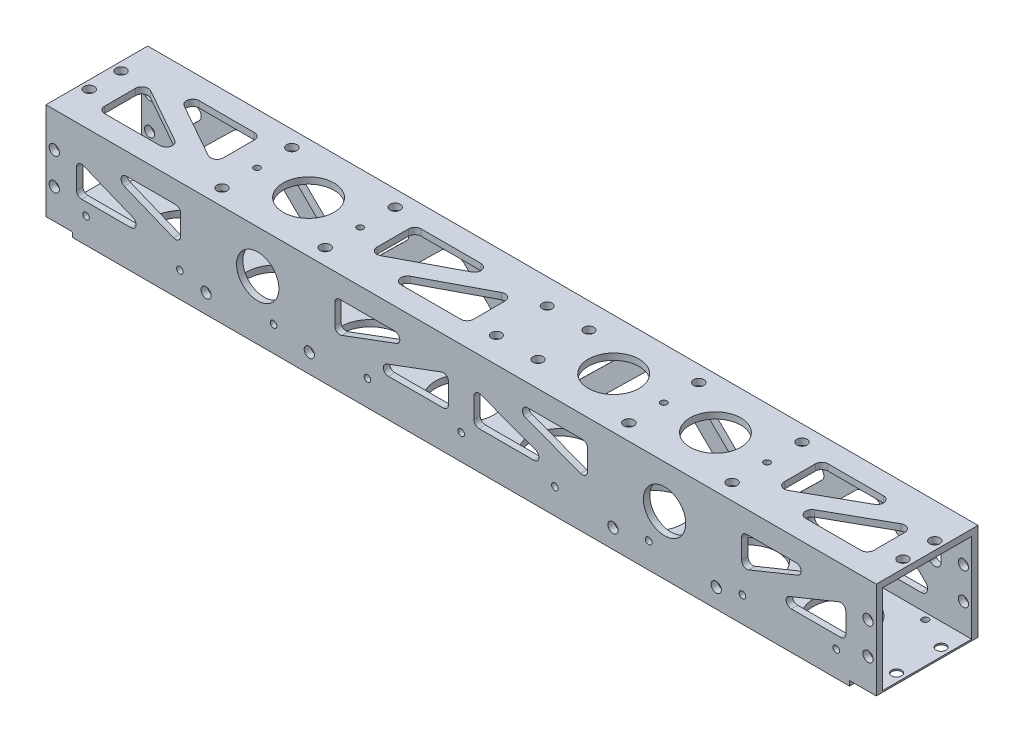
SolidWorks part; units mm, degrees
material "6061-T6 (SS)"
ref_plane "Front Plane" through (0, 0, 0) normal (0, 0, 1) x (1, 0, 0)
ref_plane "Top Plane" through (0, 0, 0) normal (0, 1, 0) x (1, 0, 0)
ref_plane "Right Plane" through (0, 0, 0) normal (1, 0, 0) x (0, 0, -1)
sketch "Sketch1" plane through (0, 0, 0) normal (1, 0, 0) x (0, 0, -1)
  line L0 (-22.225, 22.225) -> (22.225, 22.225)
  line L1 (-25.4, -25.4) -> (25.4, -25.4)
  line L2 (-25.4, -25.4) -> (-25.4, 25.4)
  line L3 (-25.4, 25.4) -> (25.4, 25.4)
  line L4 (25.4, -25.4) -> (25.4, 25.4)
  line L5 (-25.4, -25.4) -> (25.4, 25.4) construction
  line L6 (-25.4, 25.4) -> (25.4, -25.4) construction
  line L7 (22.225, -22.225) -> (22.225, 22.225)
  line L8 (-22.225, -22.225) -> (22.225, -22.225)
  line L9 (-22.225, -22.225) -> (-22.225, 22.225)
  point P0 (0, 0)
  dimension "D1" = 50.8
  dimension "D2" = 3.175
extrude "Boss-Extrude1" add sketch "Sketch1" along normal mid plane 414.655
sketch "Sketch2" plane through (0, 0, 0) normal (0, 0, 1) x (1, 0, 0)
  line L1 (-207.3275, -25.4) -> (-193.9925, -25.4)
  line L2 (-207.3275, -25.4) -> (-207.3275, -22.987)
  line L3 (-207.3275, -22.987) -> (-193.9925, -22.987)
  line L4 (-193.9925, -25.4) -> (-193.9925, -22.987)
  line L5 (207.3275, -25.4) -> (193.9925, -25.4)
  line L6 (207.3275, -25.4) -> (207.3275, -22.987)
  line L7 (207.3275, -22.987) -> (193.9925, -22.987)
  line L8 (193.9925, -25.4) -> (193.9925, -22.987)
  dimension "D1" = 2.413
  dimension "D2" = 13.335
extrude "Cut-Extrude1" cut sketch "Sketch2" against normal through all both and the other way through all
hole_wizard "#10 Clearance Hole1" positions "Sketch3" profile "Sketch4" hole size "#10" standard "ANSI Inch"
sketch "Sketch3" plane through (0, 25.4, 0) normal (0, -1, 0) x (-1, 0, 0)
  line L1 (-127.381, 17.4625) -> (127.381, 17.4625)
  line L2 (-127.381, 17.4625) -> (-127.381, -17.4625)
  line L3 (-127.381, -17.4625) -> (127.381, -17.4625)
  line L4 (127.381, 17.4625) -> (127.381, -17.4625)
  line L5 (-127.381, 17.4625) -> (127.381, -17.4625) construction
  line L6 (-127.381, -17.4625) -> (127.381, 17.4625) construction
  line L8 (-75.819, -17.4625) -> (75.819, -17.4625)
  line L9 (-75.819, -17.4625) -> (-75.819, 17.4625)
  line L10 (-75.819, 17.4625) -> (75.819, 17.4625)
  line L11 (75.819, -17.4625) -> (75.819, 17.4625)
  line L12 (-75.819, -17.4625) -> (75.819, 17.4625) construction
  line L13 (-75.819, 17.4625) -> (75.819, -17.4625) construction
  line L14 (-75.819, -17.4625) -> (-127.381, 17.4625) construction
  line L16 (0, 30.2564) -> (0, -42.6417) construction
  line L18 (-101.6, 0) -> (-101.6, 17.4625) construction
  point P2 (127.381, -17.4625)
  point P5 (-127.381, 17.4625)
  point P6 (-127.381, -17.4625)
  point P7 (127.381, 17.4625)
  point P51 (0, 0)
  point P68 (75.819, 17.4625)
  point P71 (-75.819, -17.4625)
  point P72 (-75.819, 17.4625)
  point P73 (75.819, -17.4625)
  dimension "D1" = 203.2
  dimension "D2" = 34.925
  dimension "D3" = 51.562
sketch "Sketch4" plane through (-127.381, 25.4, 17.4625) normal (1, 0, 0) x (0, 0, 1)
  line L0 (0, 0) -> (0, 4.7078)
  line L1 (0, 4.7078) -> (2.5527, 3.174)
  line L2 (2.5527, 3.174) -> (2.5527, 0)
  line L5 (2.5527, 0) -> (0, 0)
  line L10 (0, 4.7078) -> (-2.5527, 3.174) construction
  line L11 (0, -6.35) -> (0, 107.95) construction
  dimension "Hole Dia." = 5.1054
  dimension "Hole Depth" = 3.174
  dimension "Drill Angle" = 118
sketch "Sketch5" plane through (0, -25.4, 0) normal (0, -1, 0) x (1, 0, 0)
  circle A0 centre (-127.381, 17.4625) radius 4.7625
  circle A1 centre (-127.381, -17.4625) radius 4.7625
  circle A2 centre (127.381, -17.4625) radius 4.7625
  circle A3 centre (127.381, 17.4625) radius 4.7625
  circle A4 centre (-75.819, 17.4625) radius 4.7625
  circle A5 centre (-75.819, -17.4625) radius 4.7625
  circle A6 centre (75.819, -17.4625) radius 4.7625
  circle A7 centre (75.819, 17.4625) radius 4.7625
  dimension "D1" = 9.525
extrude "Cut-Extrude2" [suppressed] cut sketch "Sketch5" against normal up to next
hole_wizard "#10 Clearance Hole2" positions "Sketch6" profile "Sketch7" hole size "#10" standard "ANSI Inch"
sketch "Sketch6" plane through (0, 0, 25.4) normal (0, 0, -1) x (-1, 0, 0)
  line L0 (-127.381, 25.4) -> (-127.381, -25.4) construction
  line L1 (-207.3275, 25.4) -> (207.3275, 25.4) construction
  line L2 (-193.9925, -25.4) -> (193.9925, -25.4) construction
  line L4 (127.381, 25.4) -> (127.381, -25.4) construction
  line L6 (-124.8283, 25.4) -> (-129.9337, 25.4) construction
  line L7 (129.9337, 25.4) -> (124.8283, 25.4) construction
  line L8 (-75.819, 25.4) -> (-75.819, -25.4) construction
  line L10 (75.819, 25.4) -> (75.819, -25.4) construction
  line L15 (78.3717, 25.4) -> (73.2663, 25.4) construction
  line L16 (-73.2663, 25.4) -> (-78.3717, 25.4) construction
  point P15 (-127.381, -15.875)
  point P17 (127.381, -15.875)
  point P49 (-75.819, -15.875)
  point P51 (75.819, -15.875)
  dimension "D1" = 9.525
sketch "Sketch7" plane through (-75.819, -15.875, 25.4) normal (1, 0, 0) x (0, -1, 0)
  line L0 (0, 0) -> (0, 3.175)
  line L1 (0, 3.175) -> (2.5527, 3.175)
  line L2 (2.5527, 3.175) -> (2.5527, 0)
  line L5 (2.5527, 0) -> (0, 0)
  line L11 (0, -6.35) -> (0, 107.95) construction
  dimension "Thru Hole Dia." = 5.1054
  dimension "Thru Hole Depth" = 3.175
hole_wizard "#10 Clearance Hole3" positions "Sketch9" profile "Sketch10" hole size "#10" standard "ANSI Inch"
sketch "Sketch9" plane through (0, 25.4, 0) normal (0, 1, 0) x (1, 0, 0)
  line L1 (-203.2, -7.9375) -> (203.2, -7.9375)
  line L2 (-203.2, -7.9375) -> (-203.2, 7.9375)
  line L3 (-203.2, 7.9375) -> (203.2, 7.9375)
  line L4 (203.2, -7.9375) -> (203.2, 7.9375)
  line L5 (-203.2, -7.9375) -> (203.2, 7.9375) construction
  line L6 (-203.2, 7.9375) -> (203.2, -7.9375) construction
  point P2 (203.2, 7.9375)
  point P5 (-203.2, -7.9375)
  point P6 (-203.2, 7.9375)
  point P7 (203.2, -7.9375)
  point P42 (0, 0)
  dimension "D1" = 15.875
  dimension "D2" = 406.4
sketch "Sketch10" plane through (203.2, 25.4, -7.9375) normal (1, 0, 0) x (0, 0, 1)
  line L0 (0, 0) -> (0, 3.175)
  line L1 (0, 3.175) -> (2.5527, 3.175)
  line L2 (2.5527, 3.175) -> (2.5527, 0)
  line L5 (2.5527, 0) -> (0, 0)
  line L11 (0, -6.35) -> (0, 107.95) construction
  dimension "Thru Hole Dia." = 5.1054
  dimension "Thru Hole Depth" = 3.175
hole_wizard "#10 Clearance Hole4" positions "Sketch11" profile "Sketch12" hole size "#10" standard "ANSI Inch" end condition through all
sketch "Sketch11" plane through (0, 0, 25.4) normal (0, 0, 1) x (1, 0, 0)
  line L1 (-203.2, 7.9375) -> (203.2, 7.9375)
  line L2 (-203.2, 7.9375) -> (-203.2, -7.9375)
  line L3 (-203.2, -7.9375) -> (203.2, -7.9375)
  line L4 (203.2, 7.9375) -> (203.2, -7.9375)
  line L5 (-203.2, 7.9375) -> (203.2, -7.9375) construction
  line L6 (-203.2, -7.9375) -> (203.2, 7.9375) construction
  line L7 (-203.2, 7.9375) -> (-203.2, 25.4) construction
  line L8 (207.3275, 25.4) -> (-207.3275, 25.4) construction
  line L10 (-200.6473, 25.4) -> (-205.7527, 25.4) construction
  point P2 (203.2, -7.9375)
  point P5 (-203.2, 7.9375)
  point P6 (-203.2, -7.9375)
  point P7 (203.2, 7.9375)
  point P54 (0, 0)
  dimension "D1" = 15.875
sketch "Sketch12" plane through (203.2, -7.9375, 25.4) normal (1, 0, 0) x (0, -1, 0)
  line L0 (0, 0) -> (0, 50.8)
  line L1 (0, 50.8) -> (2.5527, 50.8)
  line L2 (2.5527, 50.8) -> (2.5527, 0)
  line L5 (2.5527, 0) -> (0, 0)
  line L11 (0, -6.35) -> (0, 107.95) construction
  dimension "Thru Hole Dia." = 5.1054
  dimension "Thru Hole Depth" = 50.8
hole_wizard "Hole1" positions "Sketch15" profile "Sketch16" legacy end condition up to next
sketch "Sketch15" plane through (0, -25.4, 0) normal (0, -1, 0) x (-1, 0, 0)
  line L1 (187.325, -19.05) -> (-187.325, -19.05)
  line L2 (187.325, -19.05) -> (187.325, 19.05)
  line L3 (187.325, 19.05) -> (-187.325, 19.05)
  line L4 (-187.325, -19.05) -> (-187.325, 19.05)
  line L5 (187.325, -19.05) -> (-187.325, 19.05) construction
  line L6 (187.325, 19.05) -> (-187.325, -19.05) construction
  point P5 (187.325, -19.05)
  point P6 (187.325, 19.05)
  point P42 (0, 0)
  point P52 (140.4938, -19.05)
  point P53 (140.4938, 19.05)
  point P54 (93.6625, -19.05)
  point P55 (93.6625, 19.05)
  point P56 (46.8312, -19.05)
  point P57 (46.8312, 19.05)
  point P58 (0, -19.05)
  point P59 (0, 19.05)
  point P60 (-46.8312, -19.05)
  point P61 (-46.8312, 19.05)
  point P62 (-93.6625, -19.05)
  point P63 (-93.6625, 19.05)
  point P64 (-140.4938, -19.05)
  point P65 (-140.4938, 19.05)
  point P66 (-187.325, -19.05)
  point P67 (-187.325, 19.05)
  dimension "D1" = 38.1
  dimension "D2" = 374.65
  dimension "D3" = 9
sketch "Sketch16" plane through (187.325, -25.4, -19.05) normal (1, 0, 0) x (0, 0, -1)
  line L0 (0, 0) -> (0, 4.1594)
  line L1 (0, 4.1594) -> (1.6383, 3.175)
  line L2 (1.6383, 3.175) -> (1.6383, 0)
  line L4 (1.6383, 0) -> (0, 0)
  line L6 (0, 4.1594) -> (-1.6383, 3.175) construction
  line L7 (0, -4.2442) -> (0, 117.3081) construction
  dimension "Diameter" = 3.2766
  dimension "Depth" = 3.175
  dimension "Drill Angle" = 118
hole_wizard "Hole2" positions "Sketch17" profile "Sketch18" legacy
sketch "Sketch17" plane through (0, 0, 25.4) normal (0, 0, 1) x (1, 0, 0)
  line L0 (-187.325, -12.7) -> (187.325, -12.7) construction
  line L2 (0, -12.7) -> (0, 0) construction
  line L3 (193.9925, -25.4) -> (-193.9925, -25.4) construction
  line L4 (-187.325, -12.7) -> (-187.325, -25.4) construction
  line L6 (-188.9633, -25.4) -> (-185.6867, -25.4) construction
  point P1 (-187.325, -12.7)
  point P25 (-140.4938, -12.7)
  point P26 (-93.6625, -12.7)
  point P27 (-46.8312, -12.7)
  point P28 (0, -12.7)
  point P29 (46.8312, -12.7)
  point P30 (93.6625, -12.7)
  point P31 (140.4938, -12.7)
  point P32 (187.325, -12.7)
  dimension "D1" = 12.7
  dimension "D2" = 9
sketch "Sketch18" plane through (-187.325, -12.7, 25.4) normal (1, 0, 0) x (0, -1, 0)
  line L0 (0, 0) -> (0, 3.175)
  line L1 (0, 3.175) -> (1.6383, 3.175)
  line L2 (1.6383, 3.175) -> (1.6383, 0)
  line L3 (1.6383, 0) -> (0, 0)
  line L4 (0, 110) -> (0, -10) construction
  dimension "Diameter" = 3.2766
  dimension "Depth" = 3.175
sketch "Sketch19" plane through (0, 25.4, 0) normal (0, 1, 0) x (1, 0, 0)
  line L0 (-127.381, 17.4625) -> (-127.381, -17.4625) construction
  line L1 (127.381, 17.4625) -> (127.381, -17.4625) construction
  line L2 (-75.819, 17.4625) -> (-75.819, -17.4625) construction
  line L3 (75.819, 17.4625) -> (75.819, -17.4625) construction
  circle A0 centre (127.381, 0) radius 1.5748
  circle A1 centre (-127.381, 0) radius 1.5748
  circle A3 centre (-75.819, 17.4625) radius 2.5527 construction
  circle A4 centre (-75.819, 0) radius 1.5748
  circle A5 centre (75.819, 0) radius 1.5748
  dimension "D1" = 3.1496
extrude "Cut-Extrude4" cut sketch "Sketch19" against normal up to next
hole_wizard "#10 Clearance Hole5" positions "Sketch21" profile "Sketch22" hole size "#10" standard "ANSI Inch"
sketch "Sketch21" plane through (0, -22.987, 0) normal (0, -1, 0) x (-1, 0, 0)
  line L0 (-203.2, -11.1125) -> (-203.2, 11.1125) construction
  line L2 (-207.3275, 25.4) -> (-207.3275, -25.4) construction
  line L3 (-203.2, 0) -> (-207.3275, 0) construction
  line L5 (207.3275, 0) -> (203.2, 0) construction
  line L6 (207.3275, 25.4) -> (207.3275, -25.4) construction
  line L8 (203.2, -11.1125) -> (203.2, 11.1125) construction
  point P0 (-203.2, -11.1125)
  point P4 (-203.2, 11.1125)
  point P18 (203.2, -11.1125)
  point P19 (203.2, 11.1125)
  dimension "D1" = 4.1275
  dimension "D2" = 22.225
sketch "Sketch22" plane through (203.2, -22.987, 11.1125) normal (1, 0, 0) x (0, 0, -1)
  line L0 (0, 0) -> (0, 0.762)
  line L1 (0, 0.762) -> (2.4892, 0.762)
  line L2 (2.4892, 0.762) -> (2.4892, 0)
  line L5 (2.4892, 0) -> (0, 0)
  line L11 (0, -6.35) -> (0, 107.95) construction
  dimension "Thru Hole Dia." = 4.9784
  dimension "Thru Hole Depth" = 0.762
sketch "Sketch23" plane through (0, 25.4, 0) normal (0, 1, 0) x (1, 0, 0)
  line L0 (25.7175, 25.4) -> (25.7175, 12.7) construction
  line L1 (4.8895, 25.4) -> (4.8895, -25.4) construction
  line L2 (207.3275, 25.4) -> (207.3275, -25.4) construction
  line L5 (207.3275, 25.4) -> (-207.3275, 25.4) construction
  line L6 (25.7175, 12.7) -> (25.7175, -12.7) construction
  line L7 (25.7175, -12.7) -> (25.7175, -25.4) construction
  line L8 (207.3275, -25.4) -> (-207.3275, -25.4) construction
  circle A0 centre (25.7175, 12.7) radius 2.4892
  circle A1 centre (25.7175, -12.7) radius 2.4892
  circle A2 centre (4.8895, 12.7) radius 2.4892
  circle A3 centre (4.8895, -12.7) radius 2.4892
  dimension "D2" = 20.828
  dimension "D3" = 4.9784
  dimension "D1" = 25.4
  dimension "D4" = 181.61
extrude "Cut-Extrude5" cut sketch "Sketch23" against normal up to next
sketch "Sketch24" plane through (0, 25.4, 0) normal (0, 1, 0) x (1, 0, 0)
  line L0 (207.3275, 0) -> (-207.3275, 0) construction
  line L1 (-207.3275, 25.4) -> (-207.3275, -25.4) construction
  line L2 (207.3275, 25.4) -> (207.3275, -25.4) construction
  line L3 (-194.4154, 15.9125) -> (-135.5451, -17.1526) construction
  line L8 (207.3275, -25.4) -> (-207.3275, -25.4) construction
  line L9 (-75.819, -17.4625) -> (-75.819, 17.4625) construction
  line L14 (-53.6008, -14.605) -> (-7.8105, -14.605)
  line L15 (-63.119, -9.5782) -> (-63.119, 14.605)
  line L20 (-127.381, 17.4625) -> (-127.381, -17.4625) construction
  line L21 (-192.0875, -14.605) -> (-149.1579, -14.605)
  line L26 (-192.0875, -14.605) -> (-192.0875, 9.5069)
  line L27 (-183.0106, 14.605) -> (-140.081, 14.605)
  line L28 (-70.6082, -18.5603) -> (-10.0327, 13.4314) construction
  line L29 (-140.081, -9.5069) -> (-140.081, 14.605)
  line L33 (-192.0875, -14.605) -> (-140.081, 14.605) construction
  line L34 (-193.5097, 15.4038) -> (-140.081, -14.605) construction
  line L35 (-63.119, 14.605) -> (-17.3287, 14.605)
  line L36 (-7.8105, -14.605) -> (-7.8105, 9.5782)
  line L37 (-63.119, -14.605) -> (-10.0327, 13.4314) construction
  line L38 (-63.119, 14.605) -> (-7.8105, -14.605) construction
  line L39 (149.1579, -14.605) -> (192.0875, -14.605)
  line L40 (140.081, -9.5069) -> (140.081, 14.605)
  line L41 (140.081, 14.605) -> (183.0106, 14.605)
  line L42 (192.0875, -14.605) -> (192.0875, 9.5069)
  line L43 (99.9879, -37.1237) -> (192.0875, 14.605) construction
  line L44 (140.081, 14.605) -> (192.0875, -14.605) construction
  line L45 (127.381, 17.4625) -> (127.381, -17.4625) construction
  line L46 (4.8895, 25.4) -> (4.8895, -25.4) construction
  line L47 (-192.0875, 9.5069) -> (-149.1579, -14.605)
  line L48 (-183.0106, 14.605) -> (-140.081, -9.5069)
  line L49 (-53.6008, -14.605) -> (-7.8105, 9.5782)
  line L50 (-63.119, -9.5782) -> (-17.3287, 14.605)
  line L51 (149.1579, -14.605) -> (192.0875, 9.5069)
  line L52 (140.081, -9.5069) -> (183.0106, 14.605)
  line L53 (-196.5921, 12.0369) -> (-137.7218, -21.0282) construction
  line L54 (-192.2386, 19.788) -> (-133.3683, -13.2771) construction
  line L55 (-72.6841, -14.6298) -> (-12.1085, 17.3619) construction
  line L56 (-68.5324, -22.4908) -> (-7.9569, 9.5009) construction
  line L57 (97.8112, -33.2482) -> (189.9108, 18.4805) construction
  line L58 (102.1646, -40.9993) -> (194.2642, 10.7295) construction
  point P7 (-35.4648, 0)
  point P14 (166.0842, 0)
  point P18 (-166.0843, 0)
  point P56 (-138.1125, -15.875)
  point P59 (0, 0)
  point P60 (0, 0)
  point P61 (-65.0875, -14.9976)
  point P63 (0, 0)
  point P64 (0, 0)
  dimension "D4" = 12.7
  dimension "D1" = 10.795
  dimension "D2" = 12.7
  dimension "D3" = 15.24
  dimension "D5" = 12.7
  dimension "D6" = 15.24
  dimension "D7" = 12.7
  dimension "D8" = 4.445
  dimension "D9" = 4.445
  dimension "D10" = 4.445
  dimension "D11" = 4.445
  dimension "D12" = 4.445
  dimension "D13" = 4.445
extrude "Cut-Extrude7" cut sketch "Sketch24" against normal up to next
fillet "Fillet1" radius 3.175 18 edges at (149.1579, 23.8125, 14.605) (192.0875, 23.8125, -9.5069) (192.0875, 23.8125, 14.605) (140.081, 23.8125, -14.605) (183.0106, 23.8125, -14.605) (140.081, 23.8125, 9.5069) (-7.8105, 23.8125, 14.605) (-53.6008, 23.8125, 14.605) (-7.8105, 23.8125, -9.5782) (-17.3287, 23.8125, -14.605) (-63.119, 23.8125, 9.5782) (-63.119, 23.8125, -14.605) (-183.0106, 23.8125, -14.605) (-140.081, 23.8125, 9.5069) (-140.081, 23.8125, -14.605) (-149.1579, 23.8125, 14.605) (-192.0875, 23.8125, 14.605) (-192.0875, 23.8125, -9.5069)
sketch "Sketch25" plane through (0, 0, 25.4) normal (0, 0, 1) x (1, 0, 0)
  line L0 (-207.3275, 4.0323) -> (207.3275, 4.0323) construction
  line L1 (-192.0875, 9.8066) -> (-151.8824, -6.5405)
  line L2 (-192.0875, -6.5405) -> (-151.8824, -6.5405)
  line L3 (-192.0875, -6.5405) -> (-192.0875, 9.8066)
  line L4 (-180.2861, 14.605) -> (-140.081, 14.605)
  line L5 (0, 25.4) -> (0, -6.5405) construction
  line L6 (207.3275, 25.4) -> (-207.3275, 25.4) construction
  line L7 (-140.081, -1.7421) -> (-140.081, 14.605)
  line L12 (-207.3275, 25.4) -> (-207.3275, -22.987) construction
  line L13 (207.3275, 25.4) -> (207.3275, -22.987) construction
  line L14 (-192.0875, -6.5405) -> (-140.081, 14.605) construction
  line L15 (-194.5446, 15.604) -> (-140.081, -6.5405) construction
  line L16 (-50.3846, -6.5405) -> (-6.35, -6.5405)
  line L17 (-63.119, -1.7972) -> (-63.119, 14.605)
  line L18 (-63.119, 14.605) -> (-19.0844, 14.605)
  line L19 (-6.35, -6.5405) -> (-6.35, 9.8617)
  line L20 (-63.119, -6.5405) -> (-8.9668, 13.6303) construction
  line L21 (-63.119, 14.605) -> (-6.35, -6.5405) construction
  line L22 (-50.3846, -6.5405) -> (-6.35, 9.8617)
  line L23 (-180.2861, 14.605) -> (-140.081, -1.7421)
  line L24 (-63.119, -1.7972) -> (-19.0844, 14.605)
  line L25 (-196.2188, 11.4864) -> (-141.7552, -10.6582) construction
  line L26 (-192.8704, 19.7217) -> (-138.4068, -2.4228) construction
  line L27 (-69.2935, -4.0971) -> (-0.9024, 21.3775) construction
  line L28 (-66.1904, -12.4279) -> (2.2007, 13.0466) construction
  line L29 (-67.742, -8.2625) -> (0.6491, 17.2121) construction
  point P10 (-25.3784, 4.3498)
  point P11 (-166.0842, 4.0322)
  point P38 (-12.5015, 27.5182)
  point P39 (-65.0875, 35.6755)
  point P40 (-65.0875, 17.2142)
  point P41 (-8.842, 13.2741)
  point P44 (-65.0875, -3.8039)
  point P45 (-72.2837, -6.5405)
  point P46 (-63.829, -4.0224)
  point P47 (0, 0)
  point P48 (-61.7906, -8.0297)
  point P49 (-19.2931, 13.9663)
  point P50 (-63.246, -7.491)
  point P51 (0, 0)
  dimension "D8" = 4.445
  dimension "D1" = 31.9405
  dimension "D2" = 10.795
  dimension "D3" = 15.24
  dimension "D4" = 12.7
  dimension "D5" = 12.7
  dimension "D6" = 6.35
  dimension "D7" = 4.445
extrude "Cut-Extrude8" cut sketch "Sketch25" against normal up to next
mirror "Mirror1" about plane through (0, 0, 0) normal (1, 0, 0) of "Cut-Extrude8"
fillet "Fillet2" radius 2.54 24 edges at (-140.081, -1.7421, 23.8125) (-180.2861, 14.605, 23.8125) (-140.081, 14.605, 23.8125) (-6.35, -6.5405, 23.8125) (-50.3846, -6.5405, 23.8125) (-6.35, 9.8617, 23.8125) (-19.0844, 14.605, 23.8125) (-63.119, -1.7972, 23.8125) (-63.119, 14.605, 23.8125) (-151.8824, -6.5405, 23.8125) (-192.0875, -6.5405, 23.8125) (-192.0875, 9.8066, 23.8125) (151.8824, -6.5405, 23.8125) (192.0875, 9.8066, 23.8125) (192.0875, -6.5405, 23.8125) (63.119, -1.7972, 23.8125) (19.0844, 14.605, 23.8125) (63.119, 14.605, 23.8125) (50.3846, -6.5405, 23.8125) (180.2861, 14.605, 23.8125) (140.081, -1.7421, 23.8125) (140.081, 14.605, 23.8125) (6.35, -6.5405, 23.8125) (6.35, 9.8617, 23.8125)
sketch "Sketch26" plane through (0, 0, -25.4) normal (0, 0, -1) x (-1, 0, 0)
  line L0 (-193.9925, -25.4) -> (193.9925, -25.4) construction
  line L1 (-207.3275, 25.4) -> (207.3275, 25.4) construction
  line L2 (-207.3275, 25.4) -> (-207.3275, -25.4) construction
  line L3 (-207.3275, -25.4) -> (207.3275, -25.4) construction
  line L8 (-155.4956, 31.6239) -> (-103.6637, -19.1761) construction
  line L9 (-150.8317, 14.605) -> (-121.0284, -14.605)
  line L10 (-86.2991, -14.605) -> (-56.4958, 14.605)
  line L27 (207.3275, 25.4) -> (207.3275, -25.4) construction
  line L28 (-207.3275, -25.4) -> (-155.4956, 25.4) construction
  line L33 (-155.4956, 25.4) -> (-103.6637, -25.4) construction
  line L34 (-103.6637, -25.4) -> (-51.8319, 25.4) construction
  line L35 (-51.8319, 25.4) -> (0, -25.4) construction
  line L36 (0, -25.4) -> (51.8319, 25.4) construction
  line L37 (51.8319, 25.4) -> (103.6637, -25.4) construction
  line L38 (103.6637, -25.4) -> (155.4956, 25.4) construction
  line L39 (155.4956, 25.4) -> (207.3275, -25.4) construction
  line L40 (-47.1679, 14.605) -> (-17.3646, -14.605)
  line L41 (17.3646, -14.605) -> (47.1679, 14.605)
  line L42 (56.4958, 14.605) -> (86.2991, -14.605)
  line L43 (155.4956, 31.6239) -> (210.4388, -22.2255) construction
  line L44 (160.1596, 14.605) -> (189.9629, -14.605)
  line L45 (-189.9629, -14.605) -> (-160.1596, 14.605)
  line L46 (-138.131, 14.605) -> (-108.3277, -14.605)
  line L47 (-98.9998, -14.605) -> (-69.1965, 14.605)
  line L48 (-34.4673, 14.605) -> (-4.6639, -14.605)
  line L49 (4.6639, -14.605) -> (34.4673, 14.605)
  line L50 (155.4956, 19.1761) -> (204.2162, -28.5745) construction
  line L51 (108.3277, -14.605) -> (138.131, 14.605)
  line L52 (172.8602, 14.605) -> (192.0875, -4.2395)
  line L53 (-207.3275, 0) -> (207.3275, 0) construction
  line L54 (-192.0875, -4.2395) -> (-172.8602, 14.605)
  line L55 (-189.9629, -14.605) -> (-121.0284, -14.605)
  line L57 (-192.0875, 14.605) -> (-172.8602, 14.605)
  line L59 (-210.4388, -22.2255) -> (-155.4956, 31.6239) construction
  line L60 (-204.2162, -28.5745) -> (-155.4956, 19.1761) construction
  line L61 (-155.4956, 19.1761) -> (-103.6637, -31.6239) construction
  line L62 (0, -19.1761) -> (51.8319, 31.6239) construction
  line L63 (-103.6637, -31.6239) -> (-51.8319, 19.1761) construction
  line L64 (-103.6637, -19.1761) -> (-51.8319, 31.6239) construction
  line L65 (-51.8319, 31.6239) -> (0, -19.1761) construction
  line L66 (-51.8319, 19.1761) -> (0, -31.6239) construction
  line L67 (0, -31.6239) -> (51.8319, 19.1761) construction
  line L68 (51.8319, 19.1761) -> (103.6637, -31.6239) construction
  line L69 (69.1965, 14.605) -> (98.9998, -14.605)
  line L70 (51.8319, 31.6239) -> (103.6637, -19.1761) construction
  line L71 (103.6637, -19.1761) -> (155.4956, 31.6239) construction
  line L72 (121.0284, -14.605) -> (150.8317, 14.605)
  line L73 (103.6637, -31.6239) -> (155.4956, 19.1761) construction
  line L74 (192.0875, -4.2395) -> (192.0875, 14.605)
  line L75 (172.8602, 14.605) -> (192.0875, 14.605)
  line L76 (150.8317, 14.605) -> (160.1596, 14.605)
  line L77 (121.0284, -14.605) -> (189.9629, -14.605)
  line L78 (98.9998, -14.605) -> (108.3277, -14.605)
  line L79 (69.1965, 14.605) -> (138.131, 14.605)
  line L80 (47.1679, 14.605) -> (56.4958, 14.605)
  line L81 (17.3646, -14.605) -> (86.2991, -14.605)
  line L82 (-4.6639, -14.605) -> (4.6639, -14.605)
  line L83 (-34.4673, 14.605) -> (34.4673, 14.605)
  line L84 (-56.4958, 14.605) -> (-47.1679, 14.605)
  line L85 (-86.2991, -14.605) -> (-17.3646, -14.605)
  line L86 (-108.3277, -14.605) -> (-98.9998, -14.605)
  line L87 (-138.131, 14.605) -> (-69.1965, 14.605)
  line L88 (-160.1596, 14.605) -> (-150.8317, 14.605)
  line L89 (-192.0875, -4.2395) -> (-192.0875, 14.605)
  point P38 (-194.6275, 0)
  dimension "D9" = 4.445
  dimension "D5" = 10.795
  dimension "D1" = 4.445
  dimension "D2" = 4.445
  dimension "D3" = 4.445
  dimension "D4" = 15.24
  dimension "D6" = 4.445
  dimension "D7" = 4.445
  dimension "D8" = 15.24
  dimension "D10" = 10.795
extrude "Cut-Extrude9" cut sketch "Sketch26" against normal up to next
fillet "Fillet3" radius 3.175 34 edges at (-192.0875, 14.605, -23.8125) (-192.0875, -4.2395, -23.8125) (-172.8602, 14.605, -23.8125) (-17.3646, -14.605, -23.8125) (-47.1679, 14.605, -23.8125) (-56.4958, 14.605, -23.8125) (-86.2991, -14.605, -23.8125) (34.4673, 14.605, -23.8125) (-34.4673, 14.605, -23.8125) (-4.6639, -14.605, -23.8125) (4.6639, -14.605, -23.8125) (-160.1596, 14.605, -23.8125) (-189.9629, -14.605, -23.8125) (-121.0284, -14.605, -23.8125) (-150.8317, 14.605, -23.8125) (-138.131, 14.605, -23.8125) (-108.3277, -14.605, -23.8125) (-98.9998, -14.605, -23.8125) (-69.1965, 14.605, -23.8125) (160.1596, 14.605, -23.8125) (150.8317, 14.605, -23.8125) (121.0284, -14.605, -23.8125) (189.9629, -14.605, -23.8125) (192.0875, -4.2395, -23.8125) (17.3646, -14.605, -23.8125) (86.2991, -14.605, -23.8125) (56.4958, 14.605, -23.8125) (47.1679, 14.605, -23.8125) (69.1965, 14.605, -23.8125) (98.9998, -14.605, -23.8125) (108.3277, -14.605, -23.8125) (138.131, 14.605, -23.8125) (172.8602, 14.605, -23.8125) (192.0875, 14.605, -23.8125)
sketch "Sketch27" plane through (0, -25.4, 0) normal (0, -1, 0) x (1, 0, 0)
  line L0 (-193.9925, 19.05) -> (193.9925, 19.05) construction
  line L1 (-193.9925, -25.4) -> (-193.9925, 25.4) construction
  line L2 (193.9925, -25.4) -> (193.9925, 25.4) construction
  line L3 (-187.325, 19.05) -> (187.325, 19.05) construction
  line L4 (-193.9925, -19.05) -> (193.9925, -19.05) construction
  line L5 (-193.9925, -25.4) -> (-193.9925, 25.4) construction
  line L6 (193.9925, -25.4) -> (193.9925, 25.4) construction
  line L7 (-187.325, -19.05) -> (187.325, -19.05) construction
  line L8 (-165.1, 0) -> (165.1, 0) construction
  line L10 (193.9925, 25.4) -> (-193.9925, 25.4) construction
  circle A8 centre (-165.1, 0) radius 14.605
  circle A9 centre (-117.9286, 0) radius 14.605
  circle A10 centre (-70.7571, 0) radius 14.605
  circle A11 centre (-23.5857, 0) radius 14.605
  circle A12 centre (23.5857, 0) radius 14.605
  circle A13 centre (70.7571, 0) radius 14.605
  circle A14 centre (117.9286, 0) radius 14.605
  circle A15 centre (165.1, 0) radius 14.605
  point P19 (0, 0)
  dimension "D1" = 8
  dimension "D3" = 10.795
  dimension "D2" = 330.2
extrude "Cut-Extrude10" cut sketch "Sketch27" against normal up to next
sketch "Sketch28" plane through (0, 25.4, 0) normal (0, 1, 0) x (1, 0, 0)
  line L0 (127.381, 17.4625) -> (75.819, -17.4625) construction
  line L2 (207.3275, 25.4) -> (-207.3275, 25.4) construction
  line L3 (25.7175, 12.7) -> (25.7175, -12.7) construction
  line L4 (25.7175, 0) -> (75.819, 0) construction
  line L5 (-75.819, 17.4625) -> (-127.381, -17.4625) construction
  circle A0 centre (101.6, 0) radius 12.7
  circle A1 centre (50.7683, 0) radius 12.7
  circle A2 centre (-101.6, 0) radius 12.7
  point P23 (-101.6, 0)
  dimension "D1" = 12.7
extrude "Cut-Extrude11" cut sketch "Sketch28" against normal blind 3.81
sketch "Sketch29" plane through (0, 0, 25.4) normal (0, 0, 1) x (1, 0, 0)
  line L0 (-88.9, 25.4) -> (-114.3, 25.4) construction
  line L5 (-88.9, 25.4) -> (-114.3, 25.4) construction
  line L7 (-33.1803, 14.605) -> (-60.579, 14.605) construction
  line L8 (-101.6, 4.0322) -> (-101.6, 25.4) construction
  line L9 (-36.2887, -6.5405) -> (-8.89, -6.5405) construction
  line L10 (-101.6, 4.0322) -> (101.6, 4.0322) construction
  circle A0 centre (-101.6, 4.0322) radius 10.5728
  circle A1 centre (101.6, 4.0322) radius 10.5728
  point P9 (0, 4.0322)
extrude "Cut-Extrude12" cut sketch "Sketch29" against normal blind 3.81
fillet "Fillet4" [suppressed] radius 3.175
